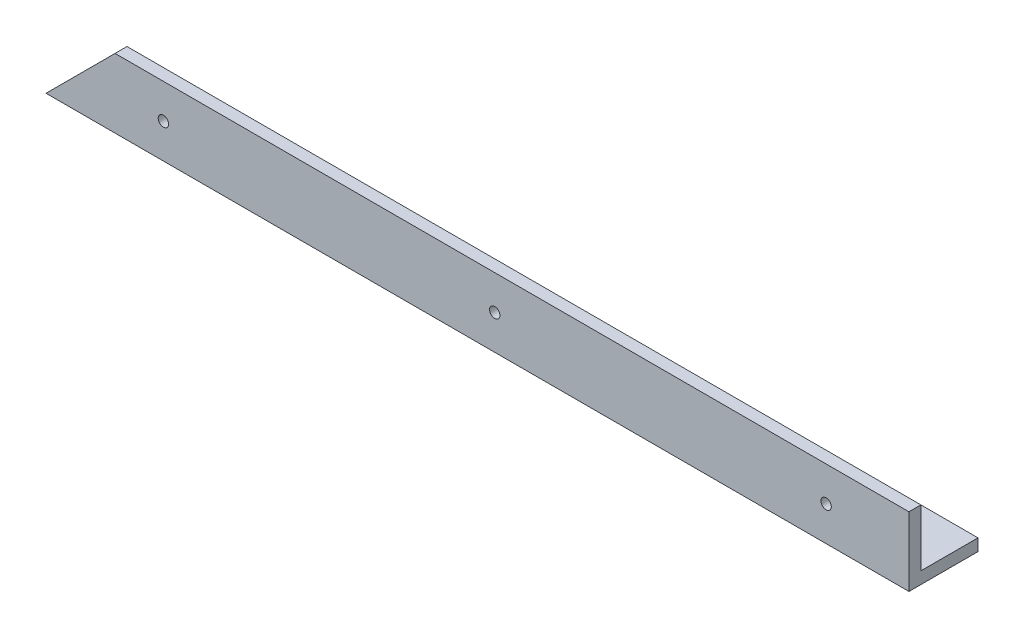
SolidWorks part; units mm, degrees
ref_plane "Front Plane" through (0, 0, 0) normal (0, 0, 1) x (1, 0, 0)
ref_plane "Top Plane" through (0, 0, 0) normal (0, 1, 0) x (1, 0, 0)
ref_plane "Right Plane" through (0, 0, 0) normal (1, 0, 0) x (0, 0, -1)
sketch "Sketch1" plane through (0, 0, 0) normal (1, 0, 0) x (0, 0, -1)
  line L0 (0, 0) -> (20, 0)
  line L1 (20, 0) -> (20, 3.4612)
  line L2 (20, 3.4612) -> (3.4612, 3.4612)
  line L3 (3.4612, 3.4612) -> (3.4612, 20)
  line L4 (3.4612, 20) -> (0, 20)
  line L5 (0, 20) -> (0, 0)
  dimension "D1" = 3.4612
  dimension "D2" = 20
extrude "Boss-Extrude1" add sketch "Sketch1" along normal blind 250
sketch "Sketch2" plane through (0, 0, 0) normal (0, 0, -1) x (1, 0, 0)
  line L1 (10, -10) -> (250, -10) construction
  line L4 (0, 0) -> (0, -20)
  line L5 (250, -20) -> (0, -20) construction
  line L6 (0, -20) -> (20, -20)
  line L7 (20, -20) -> (0, 0)
  line L9 (250, -20) -> (250, 0) construction
  circle A0 centre (130, -10) radius 1.5
  circle A1 centre (34, -10) radius 1.5
  circle A2 centre (226, -10) radius 1.5
  dimension "D1" = 3
  dimension "D2" = 96
  dimension "D3" = 96
extrude "Cut-Extrude1" cut sketch "Sketch2" along normal through all
sketch "Sketch3" plane through (0, 0, 0) normal (0, -1, 0) x (1, 0, 0)
  line L0 (12, -20) -> (0, -20)
  line L1 (0, -20) -> (0, -8)
  circle A1 centre (185, -9) radius 1.5 construction
  circle A2 centre (107, -9) radius 1.5 construction
  circle A3 centre (29, -9) radius 1.5 construction
  arc A4 (0, -8) -> (12, -20) centre (12, -8) ccw construction
  circle A5 centre (185, -9) radius 1.5
  circle A6 centre (107, -9) radius 1.5
  circle A7 centre (29, -9) radius 1.5
  arc A8 (0, -8) -> (12, -20) centre (12, -8) ccw
extrude "Cut-Extrude2" cut sketch "Sketch3" against normal through all
